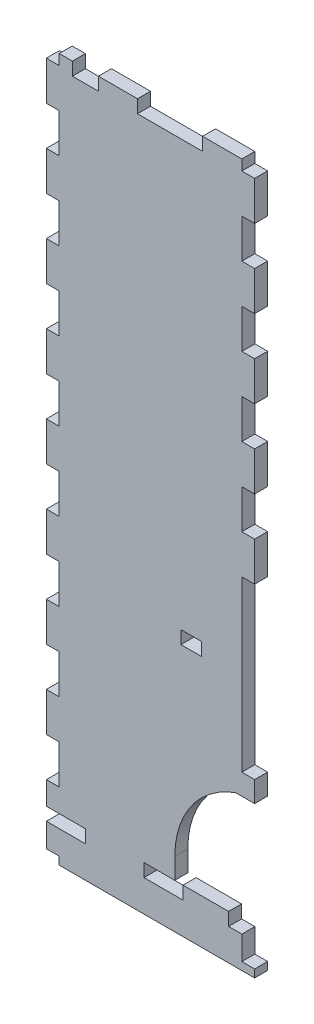
SolidWorks part; units mm, degrees
material "Balsa"
ref_plane "Plan de face" through (0, 0, 0) normal (0, 0, 1) x (1, 0, 0)
ref_plane "Plan de dessus" through (0, 0, 0) normal (0, 1, 0) x (1, 0, 0)
ref_plane "Plan de droite" through (0, 0, 0) normal (1, 0, 0) x (0, 0, -1)
sketch "Esquisse1" plane through (0, 0, 0) normal (0, 0, 1) x (1, 0, 0)
  line L0 (49.3309, 25.1093) -> (120.4109, 25.1093) construction
  line L1 (0, 0) -> (80, 0)
  line L2 (0, 0) -> (0, 270)
  line L3 (0, 270) -> (80, 270)
  line L4 (80, 59.7791) -> (80, 270)
  line L5 (49.3309, 25.1093) -> (49.3309, 17.15)
  line L6 (49.3309, 17.15) -> (80, 17.15)
  line L7 (80, 17.15) -> (80, 0)
  ellipse E0 centre (84.8709, 25.1093) end of major axis (120.4109, 25.1093) minor radius 35 (49.3309, 25.1093) -> (80, 59.7791) cw
  point P5 (84.8709, 25.1093)
  dimension "D1" = 80
  dimension "D2" = 270
  dimension "D3" = 80
  dimension "D4" = 70
  dimension "D5" = 71.08
extrude "Boss.-Extru.1" add sketch "Esquisse1" along normal blind 5
sketch "Esquisse2" plane through (0, 0, 5) normal (0, 0, 1) x (1, 0, 0)
  line L0 (80, 0) -> (80, 17.15) construction
  line L1 (51.6797, 101.7504) -> (59.6797, 101.7504)
  line L2 (51.6797, 101.7504) -> (51.6797, 96.7504)
  line L3 (51.6797, 96.7504) -> (59.6797, 96.7504)
  line L4 (59.6797, 101.7504) -> (59.6797, 96.7504)
  line L5 (75.08, 12.15) -> (70, 12.15)
  line L6 (80, 17.15) -> (80, 3)
  line L7 (80, 3) -> (75.08, 3)
  line L8 (75.08, 12.15) -> (75.08, 3)
  line L9 (80, 59.7791) -> (80, 270) construction
  line L10 (0, 0) -> (80, 0) construction
  line L11 (70, 12.15) -> (70, 17.15)
  line L12 (80, 17.15) -> (49.3309, 17.15) construction
  line L13 (70, 17.15) -> (80, 17.15)
  line L14 (0, 270) -> (0, 0) construction
  line L15 (37.5, 17.15) -> (52.5, 17.15)
  line L16 (37.5, 17.15) -> (37.5, 12.15)
  line L17 (37.5, 12.15) -> (52.5, 12.15)
  line L18 (52.5, 17.15) -> (52.5, 12.15)
  line L19 (15, 17.15) -> (0, 17.15)
  line L20 (15, 17.15) -> (15, 12.15)
  line L21 (15, 12.15) -> (0, 12.15)
  line L22 (0, 17.15) -> (0, 12.15)
  line L23 (80, 131) -> (75.08, 131)
  line L24 (0, 0) -> (4.92, 0)
  line L25 (0, 0) -> (0, 3)
  line L26 (0, 3) -> (4.92, 3)
  line L27 (4.92, 0) -> (4.92, 3)
  line L28 (80, 131) -> (80, 66)
  line L29 (80, 66) -> (75.08, 66)
  line L30 (75.08, 131) -> (75.08, 66)
  line L31 (0, 0) -> (80, 0) construction
  line L32 (80, 191) -> (75.08, 191)
  line L33 (80, 161) -> (75.08, 161)
  line L34 (80, 161) -> (80, 146)
  line L35 (80, 146) -> (75.08, 146)
  line L36 (75.08, 161) -> (75.08, 146)
  line L37 (80, 191) -> (80, 176)
  line L38 (80, 176) -> (75.08, 176)
  line L39 (75.08, 191) -> (75.08, 176)
  line L40 (80, 221) -> (75.08, 221)
  line L41 (80, 221) -> (80, 206)
  line L42 (80, 206) -> (75.08, 206)
  line L43 (75.08, 221) -> (75.08, 206)
  line L44 (80, 251) -> (75.08, 251)
  line L45 (80, 251) -> (80, 236)
  line L46 (80, 236) -> (75.08, 236)
  line L47 (75.08, 251) -> (75.08, 236)
  line L48 (80, 281) -> (75.08, 281)
  line L49 (80, 281) -> (80, 266)
  line L50 (80, 266) -> (75.08, 266)
  line L51 (75.08, 281) -> (75.08, 266)
  line L52 (0, 270) -> (0, 0) construction
  line L53 (0, 266) -> (4.92, 266)
  line L54 (0, 266) -> (0, 281)
  line L55 (0, 281) -> (4.92, 281)
  line L56 (4.92, 266) -> (4.92, 281)
  line L57 (80, 270) -> (0, 270) construction
  line L58 (0, 236) -> (4.92, 236)
  line L59 (0, 236) -> (0, 251)
  line L60 (0, 251) -> (4.92, 251)
  line L61 (4.92, 236) -> (4.92, 251)
  line L62 (0, 206) -> (4.92, 206)
  line L63 (0, 206) -> (0, 221)
  line L64 (0, 221) -> (4.92, 221)
  line L65 (4.92, 206) -> (4.92, 221)
  line L66 (0, 176) -> (4.92, 176)
  line L67 (0, 176) -> (0, 191)
  line L68 (0, 191) -> (4.92, 191)
  line L69 (4.92, 176) -> (4.92, 191)
  line L70 (0, 146) -> (4.92, 146)
  line L71 (0, 146) -> (0, 161)
  line L72 (0, 161) -> (4.92, 161)
  line L73 (4.92, 146) -> (4.92, 161)
  line L74 (0, 116) -> (4.92, 116)
  line L75 (0, 116) -> (0, 131)
  line L76 (0, 131) -> (4.92, 131)
  line L77 (4.92, 116) -> (4.92, 131)
  line L78 (0, 86) -> (4.92, 86)
  line L79 (0, 86) -> (0, 101)
  line L80 (0, 101) -> (4.92, 101)
  line L81 (4.92, 86) -> (4.92, 101)
  line L82 (0, 56) -> (4.92, 56)
  line L83 (0, 56) -> (0, 71)
  line L84 (0, 71) -> (4.92, 71)
  line L85 (4.92, 56) -> (4.92, 71)
  line L86 (0, 26) -> (4.92, 26)
  line L87 (0, 26) -> (0, 41)
  line L88 (0, 41) -> (4.92, 41)
  line L89 (4.92, 26) -> (4.92, 41)
  line L90 (80, 270) -> (0, 270) construction
  line L91 (10, 265) -> (20, 265)
  line L92 (10, 265) -> (10, 270)
  line L93 (10, 270) -> (20, 270)
  line L94 (20, 265) -> (20, 270)
  line L96 (35, 265) -> (60, 265)
  line L97 (35, 265) -> (35, 270)
  line L98 (35, 270) -> (60, 270)
  line L99 (60, 265) -> (60, 270)
  dimension "D1" = 4.92
  dimension "D2" = 3
  dimension "D3" = 10
  dimension "D4" = 5
  dimension "D5" = 5
  dimension "D6" = 15
  dimension "D7" = 27.5
  dimension "D8" = 5
  dimension "D9" = 15
  dimension "D10" = 4.92
  dimension "D11" = 3
  dimension "D12" = 4.92
  dimension "D13" = 66
  dimension "D14" = 65
  dimension "D15" = 15
  dimension "D16" = 15
  dimension "D18" = 15
  dimension "D19" = 4
  dimension "D17" = 5
  dimension "D20" = 9
extrude "Enlèv. mat.-Extru.1" cut sketch "Esquisse2" against normal blind 5
sketch "Esquisse3" plane through (0, 0, 0) normal (0, 0, -1) x (-1, 0, 0)
  line L0 (-80, 59.7791) -> (-80, 66) construction
  line L1 (-80, 61.9473) -> (-72.7194, 61.9473)
  line L2 (-80, 61.9473) -> (-80, 58)
  line L3 (-80, 58) -> (-72.7194, 58)
  line L4 (-72.7194, 61.9473) -> (-72.7194, 58)
  line L5 (-4.92, 0) -> (-80, 0) construction
  ellipse E0 centre (-84.8709, 25.1093) end of major axis (-120.4109, 25.1093) minor radius 35 (-49.3309, 25.1093) -> (-80, 59.7791) ccw construction
  dimension "D1" = 58
extrude "Boss.-Extru.2" add sketch "Esquisse3" against normal blind 5
